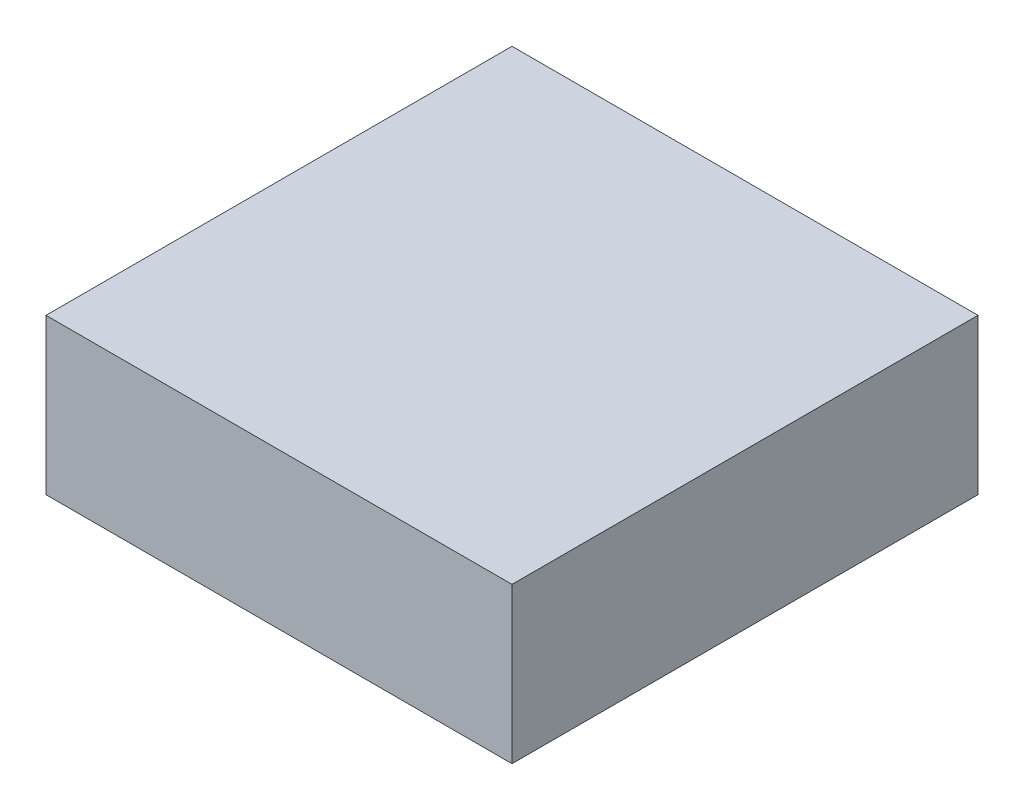
SolidWorks part; units mm, degrees
ref_plane "前视基准面" through (0, 0, 0) normal (0, 0, 1) x (1, 0, 0)
ref_plane "上视基准面" through (0, 0, 0) normal (0, 1, 0) x (1, 0, 0)
ref_plane "右视基准面" through (0, 0, 0) normal (1, 0, 0) x (0, 0, -1)
sketch "草图1" plane through (0, 0, 0) normal (0, 1, 0) x (1, 0, 0)
  line L1 (-10, -13.4118) -> (20, -13.4118)
  line L2 (-10, -13.4118) -> (-10, 16.5882)
  line L3 (-10, 16.5882) -> (20, 16.5882)
  line L4 (20, -13.4118) -> (20, 16.5882)
  line L5 (-10, -13.4118) -> (20, 16.5882) construction
  line L6 (-10, 16.5882) -> (20, -13.4118) construction
  point P0 (5, 1.5882)
  dimension "D1" = 30
  dimension "D2" = 30
extrude "凸台-拉伸1" add sketch "草图1" along normal blind 10
